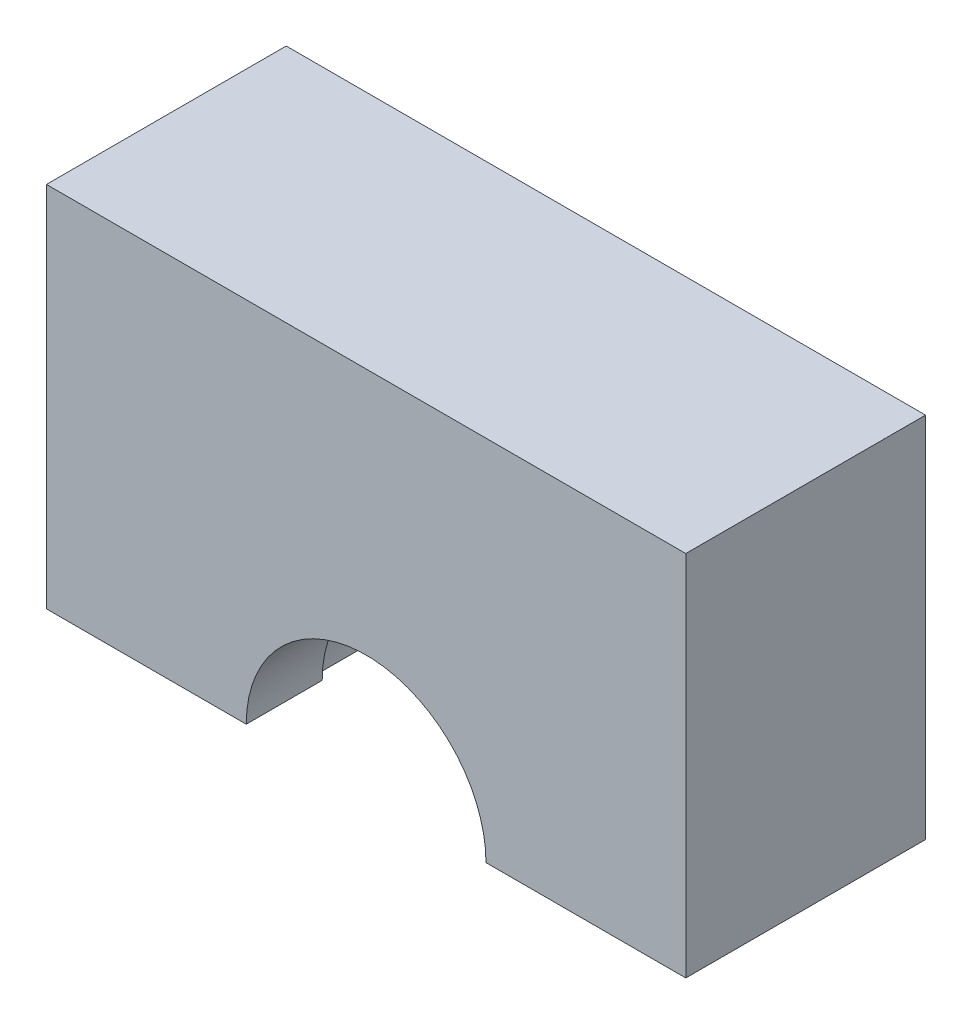
SolidWorks part; units mm, degrees
ref_plane "Front Plane" through (0, 0, 0) normal (0, 0, 1) x (1, 0, 0)
ref_plane "Top Plane" through (0, 0, 0) normal (0, 1, 0) x (1, 0, 0)
ref_plane "Right Plane" through (0, 0, 0) normal (1, 0, 0) x (0, 0, -1)
sketch "Sketch1" plane through (0, 0, 0) normal (0, 0, 1) x (1, 0, 0)
  line L0 (-20, 0) -> (-20, 23)
  line L1 (-20, 23) -> (20, 23)
  line L2 (20, 23) -> (20, 0)
  line L3 (-20, 0) -> (-7.5, 0)
  line L4 (20, 0) -> (7.5, 0)
  arc A0 (7.5, 0) -> (-7.5, 0) centre (0, 0) ccw
  dimension "D1" = 15
  dimension "D2" = 40
  dimension "D3" = 23
extrude "Boss-Extrude1" add sketch "Sketch1" along normal blind 15
sketch "Sketch2" plane through (0, 0, 0) normal (1, 0, 0) x (0, 0, -1)
  line L0 (0, 0) -> (-27.3188, 0) construction
  line L2 (-4.75, 6.4825) -> (-10.25, 6.4825)
  line L3 (-4.75, 6.4825) -> (-4.75, 8)
  line L4 (-4.75, 8) -> (-10.25, 8)
  line L5 (-10.25, 6.4825) -> (-10.25, 8)
  line L6 (-15, 23) -> (0, 23) construction
  point P11 (-7.5, 23)
  point P12 (-7.5, 8)
  dimension "D1" = 8
  dimension "D2" = 5.5
revolve "Cut-Revolve2" cut sketch "Sketch2" angle 360 about L0
